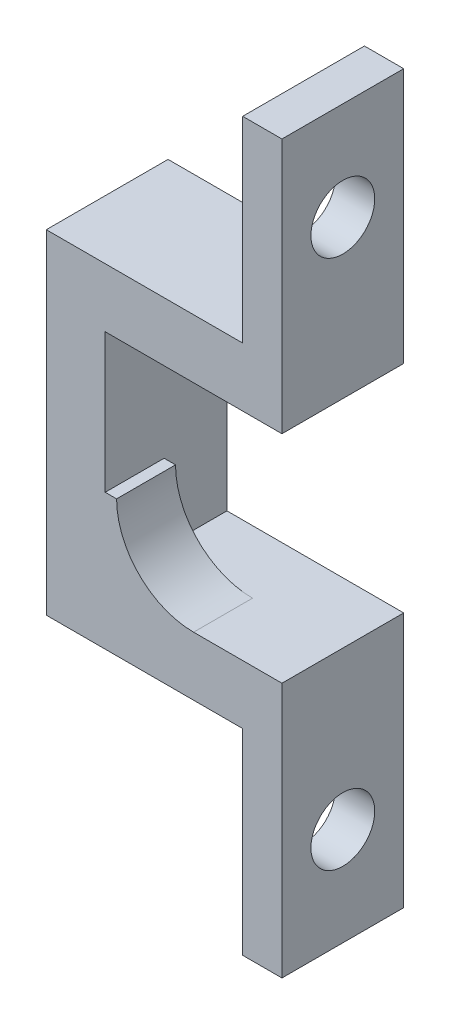
SolidWorks part; units mm, degrees
ref_plane "前基準面" through (0, 0, 0) normal (0, 0, 1) x (1, 0, 0)
ref_plane "上基準面" through (0, 0, 0) normal (0, 1, 0) x (1, 0, 0)
ref_plane "右基準面" through (0, 0, 0) normal (1, 0, 0) x (0, 0, -1)
sketch "草圖1" plane through (0, 0, 0) normal (0, 0, 1) x (1, 0, 0)
  line L0 (5.8643, -5.421) -> (5.8643, -8.421)
  line L1 (-3.1357, 5.579) -> (5.8643, 5.579)
  line L5 (5.8643, -8.421) -> (-6.1357, -8.421)
  line L6 (-6.1357, -8.421) -> (-6.1357, 8.579)
  line L7 (-6.1357, 8.579) -> (5.8643, 8.579)
  line L8 (5.8643, 8.579) -> (5.8643, 5.579)
  line L9 (-2.5557, -1.501) -> (-3.1357, -1.501)
  line L12 (-3.1357, 5.579) -> (-3.1357, -1.501)
  line L13 (1.3643, -5.421) -> (5.8643, -5.421)
  arc A1 (-2.5557, -1.501) -> (1.3643, -5.421) centre (1.3643, -1.501) ccw
  dimension "D1" = 9
  dimension "D2" = 11
  dimension "D4" = 3
extrude "填料-伸長1" add sketch "草圖1" along normal blind 3
sketch "草圖5" plane through (0, 0, 0) normal (0, 0, -1) x (-1, 0, 0)
  line L17 (3.1357, 5.579) -> (-5.8643, 5.579)
  line L18 (-5.8643, 5.579) -> (-5.8643, 8.579)
  line L19 (-5.8643, 8.579) -> (6.1357, 8.579)
  line L20 (6.1357, 8.579) -> (6.1357, -8.421)
  line L21 (6.1357, -8.421) -> (-5.8643, -8.421)
  line L22 (-5.8643, -8.421) -> (-5.8643, -5.421)
  line L23 (-5.8643, -5.421) -> (-1.3643, -5.421) construction
  line L24 (-5.8643, -8.421) -> (-5.8643, -5.421) construction
  line L25 (-5.8643, -5.421) -> (3.1357, -5.421)
  line L26 (3.1357, -5.421) -> (3.1357, 5.579)
extrude "填料-伸長5" add sketch "草圖5" along normal blind 3.2
sketch "草圖6" plane through (0, 8.579, 0) normal (0, 1, 0) x (1, 0, 0)
  line L0 (-6.1357, 3.2) -> (5.8643, 3.2) construction
  line L1 (5.8643, -3) -> (3.8643, -3)
  line L2 (5.8643, -3) -> (5.8643, 3.2)
  line L3 (5.8643, 3.2) -> (3.8643, 3.2)
  line L4 (3.8643, -3) -> (3.8643, 3.2)
  dimension "D1" = 2
extrude "填料-伸長6" add sketch "草圖6" along normal blind 10
sketch "草圖7" plane through (0, -8.421, 0) normal (0, -1, 0) x (1, 0, 0)
  line L0 (-6.1357, 3) -> (5.8643, 3) construction
  line L1 (5.8643, -3.2) -> (3.8643, -3.2)
  line L2 (5.8643, -3.2) -> (5.8643, 3)
  line L3 (5.8643, 3) -> (3.8643, 3)
  line L4 (3.8643, -3.2) -> (3.8643, 3)
  dimension "D1" = 2
extrude "填料-伸長7" add sketch "草圖7" along normal blind 10
sketch "草圖8" plane through (3.8643, 0, 0) normal (-1, 0, 0) x (0, 0, 1)
  line L0 (3, -18.421) -> (-3.2, -18.421) construction
  line L1 (-3.2, 18.579) -> (3, 18.579) construction
  line L3 (3, 18.579) -> (3, 8.579) construction
  line L4 (3, -18.421) -> (3, -8.421) construction
  circle A0 centre (-0.1, -13.421) radius 1.625
  circle A1 centre (-0.1, 13.579) radius 1.625
  dimension "D1" = 3.25
  dimension "D2" = 3.25
  dimension "D3" = 5
  dimension "D4" = 5
  dimension "D5" = 3.1
  dimension "D6" = 3.1
extrude "除料-伸長1" cut sketch "草圖8" against normal up to next
